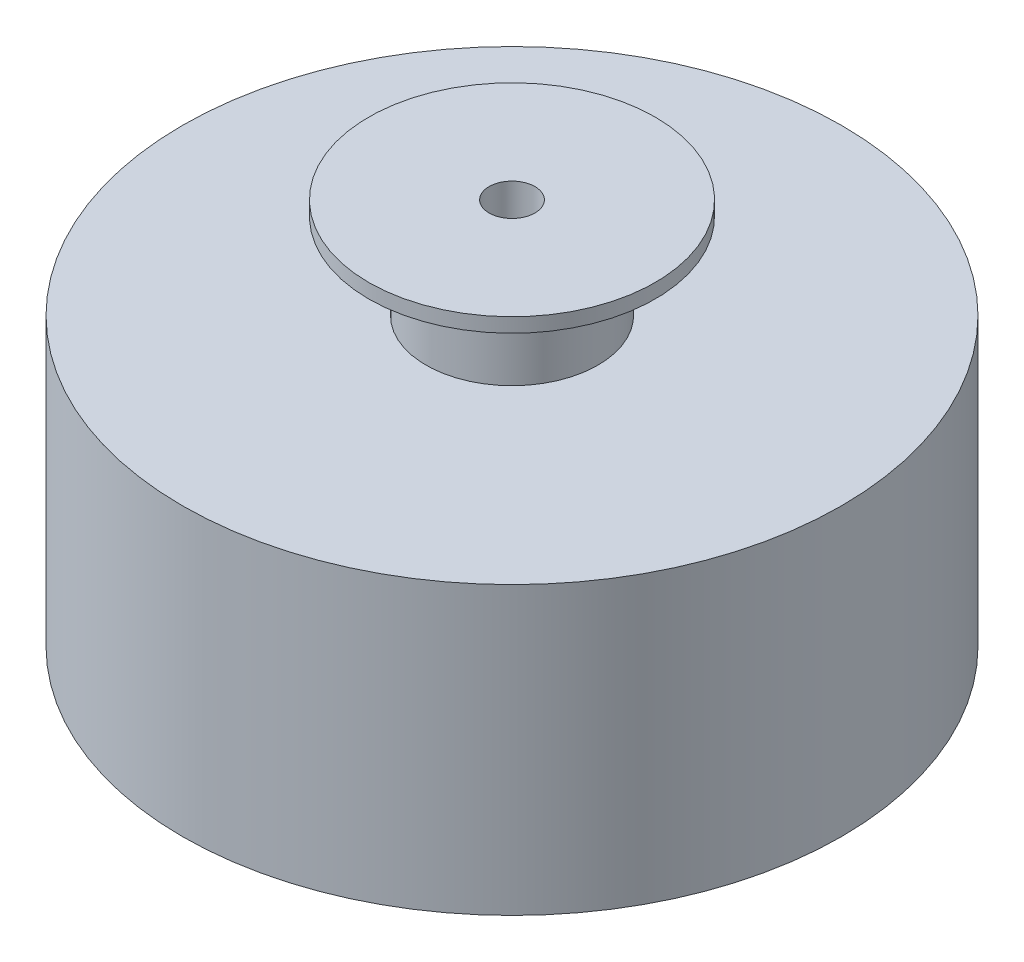
SolidWorks part; units mm, degrees
material "AISI 304"
ref_plane "Front Plane" through (0, 0, 0) normal (0, 0, 1) x (1, 0, 0)
ref_plane "Top Plane" through (0, 0, 0) normal (0, 1, 0) x (1, 0, 0)
ref_plane "Right Plane" through (0, 0, 0) normal (1, 0, 0) x (0, 0, -1)
sketch "Sketch1" plane through (0, 0, 0) normal (1, 0, 0) x (0, 0, -1)
  line L0 (0, -5577.8392) -> (0, 273314.1184) construction
  line L13 (-30, 80) -> (-50, 80)
  line L14 (-50, 80) -> (-50, 85)
  line L15 (-50, 85) -> (-8, 85)
  line L18 (-30, 50) -> (-30, 80)
  line L26 (0, 0) -> (-240.4249, 0) construction
  line L29 (-30, -50) -> (-30, -80)
  line L30 (-30, -80) -> (-50, -80)
  line L31 (-50, -80) -> (-50, -85)
  line L32 (-50, -85) -> (-8, -85)
  line L33 (-115, 50) -> (-115, -50)
  line L35 (-8, -85) -> (-8, 85)
  line L36 (-30, 50) -> (-115, 50)
  line L39 (-115, -50) -> (-30, -50)
  point P12 (-115, 0)
  dimension "D2" = 115
  dimension "D3" = 30
  dimension "D7" = 170
revolve "Revolve1" add sketch "Sketch1" angle 360 about L0
